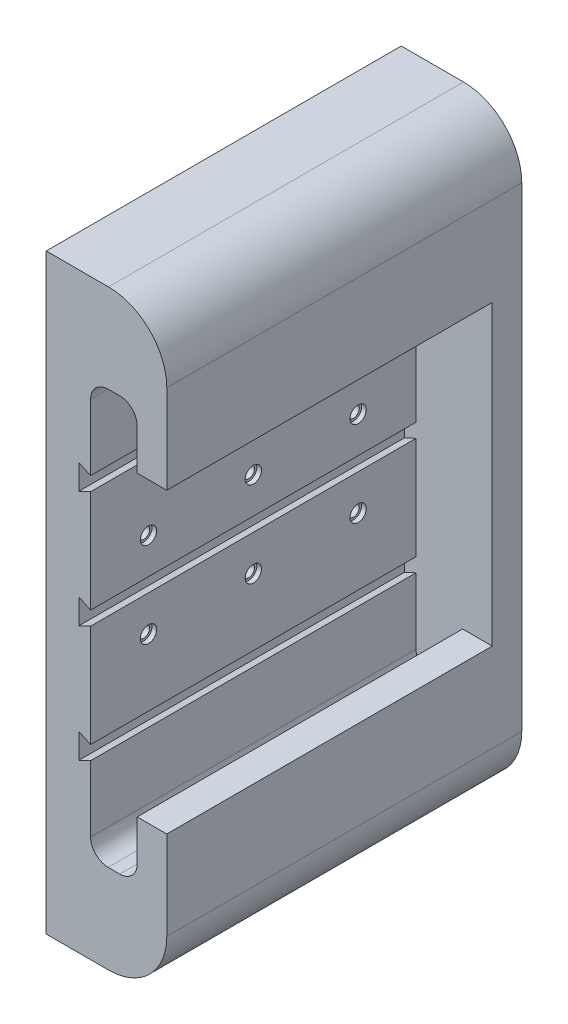
SolidWorks part; units mm, degrees
ref_plane "Front Plane" through (0, 0, 0) normal (1, 0, 0) x (0, 1, 0)
ref_plane "Top Plane" through (0, 0, 0) normal (0, 0, 1) x (0, 1, 0)
ref_plane "Right Plane" through (0, 0, 0) normal (0, 1, 0) x (-1, 0, 0)
sketch "Sketch1" plane through (0, 0, 0) normal (0, 0, 1) x (0, 1, 0)
  line L0 (-7.5, 0) -> (-85.9, 0)
  line L1 (-177.8, -25) -> (-177.8, -25.4)
  line L2 (-170.3, -20) -> (-152.8, -20)
  line L3 (-152.8, -20) -> (-152.8, -32.7)
  line L4 (-152.8, -32.7) -> (-190.9, -32.7)
  line L5 (-215.9, -7.7) -> (-215.9, 19.05)
  line L6 (-215.9, 19.05) -> (38.1, 19.05)
  line L7 (38.1, 19.05) -> (38.1, -7.7)
  line L8 (13.1, -32.7) -> (-25, -32.7)
  line L9 (-25, -32.7) -> (-25, -20)
  line L10 (-25, -20) -> (-7.5, -20)
  line L11 (0, -20) -> (0, -19.6)
  line L14 (-94.2315, 5) -> (-83.5685, 5)
  line L15 (-83.5685, 5) -> (-85.9, 0)
  line L17 (-88.9, 19.05) -> (-88.9, 5)
  line L18 (-170.3, 0) -> (-91.9, 0)
  line L20 (-91.9, 0) -> (-94.2315, 5)
  line L21 (-177.8, -12.5) -> (-177.8, -7.5)
  line L24 (0, -7.5) -> (0, -12.5)
  line L25 (-113.9, 0) -> (-113.9, 19.05) construction
  line L26 (-63.9, 0) -> (-63.9, 19.05) construction
  line L27 (-144.2315, 5) -> (-141.9, 0)
  line L28 (-133.5685, 5) -> (-144.2315, 5)
  line L29 (-135.9, 0) -> (-133.5685, 5)
  line L30 (-35.9, 0) -> (-33.5685, 5)
  line L31 (-33.5685, 5) -> (-44.2315, 5)
  line L32 (-44.2315, 5) -> (-41.9, 0)
  arc A0 (38.1, -7.7) -> (13.1, -32.7) centre (13.1, -7.7) cw
  arc A1 (-190.9, -32.7) -> (-215.9, -7.7) centre (-190.9, -7.7) cw
  arc A2 (0, -7.5) -> (-7.5, 0) centre (-7.5, -7.5) ccw
  arc A3 (-7.5, -20) -> (0, -12.5) centre (-7.5, -12.5) ccw
  arc A4 (-170.3, -20) -> (-177.8, -12.5) centre (-170.3, -12.5) cw
  arc A5 (-177.8, -7.5) -> (-170.3, 0) centre (-170.3, -7.5) cw
  point P20 (0, 0)
  point P23 (-177.8, 0)
  point P24 (-88.9, 19.05)
  point P25 (0, 0)
  dimension "D8" = 25
  dimension "D9" = 7.5
  dimension "D7" = 25
  dimension "D1" = 177.8
  dimension "D2" = 65
  dimension "D3" = 25
  dimension "D4" = 19.05
  dimension "D5" = 254
  dimension "D6" = 12.7
  dimension "D10" = 65
  dimension "D11" = 6
  dimension "D12" = 5
  dimension "D13" = 20
  dimension "D14" = 177.8
  dimension "D15" = 25
extrude "Boss-Extrude1" add sketch "Sketch1" along normal blind 152.4
sketch "Sketch2" plane through (0, 0, 0) normal (0, 0, -1) x (1, 0, 0)
  line L0 (-19.05, 215.9) -> (-19.05, -38.1)
  line L2 (32.7, 25) -> (32.7, 152.8)
  line L3 (32.7, 152.8) -> (32.7, 190.9)
  line L5 (-19.05, -38.1) -> (7.7, -38.1)
  line L6 (7.7, -38.1) -> (32.7, 25)
  line L7 (-19.05, 215.9) -> (7.7, 215.9)
  line L8 (7.7, 215.9) -> (32.7, 190.9)
extrude "Boss-Extrude2" add sketch "Sketch2" against normal blind 12.7
sketch "Sketch3" plane through (0, 0, 0) normal (1, 0, 0) x (0, 1, 0)
  line L0 (-135.9, 82.55) -> (-41.9, 82.55) construction
  line L1 (-135.9, 152.4) -> (-135.9, 12.7) construction
  line L2 (-41.9, 152.4) -> (-41.9, 12.7) construction
  line L3 (-135.9, 127.55) -> (-41.9, 127.55) construction
  line L4 (-135.9, 37.55) -> (-41.9, 37.55) construction
  line L5 (-88.9, 127.55) -> (-88.9, 37.55) construction
  circle A0 centre (-107.2857, 82.55) radius 2.5
  circle A1 centre (-107.2857, 127.55) radius 2.5
  circle A2 centre (-107.2857, 37.55) radius 2.5
  circle A3 centre (-70.5143, 37.55) radius 2.5
  circle A4 centre (-70.5143, 82.55) radius 2.5
  circle A5 centre (-70.5143, 127.55) radius 2.5
  dimension "D1" = 5
  dimension "D2" = 5
  dimension "D3" = 5
  dimension "D4" = 45
  dimension "D5" = 45
extrude "Cut-Extrude1" cut sketch "Sketch3" against normal blind 25
sketch "Sketch4" plane through (0, 0, 0) normal (1, 0, 0) x (0, 1, 0)
  circle A26 centre (-107.2857, 127.55) radius 3.5
  circle A27 centre (-107.2857, 82.55) radius 3.5
  circle A28 centre (-107.2857, 37.55) radius 3.5
  circle A29 centre (-70.5143, 37.55) radius 3.5
  circle A30 centre (-70.5143, 82.55) radius 3.5
  circle A31 centre (-70.5143, 127.55) radius 3.5
  dimension "D1" = 7
extrude "Cut-Extrude2" cut sketch "Sketch4" against normal blind 2
